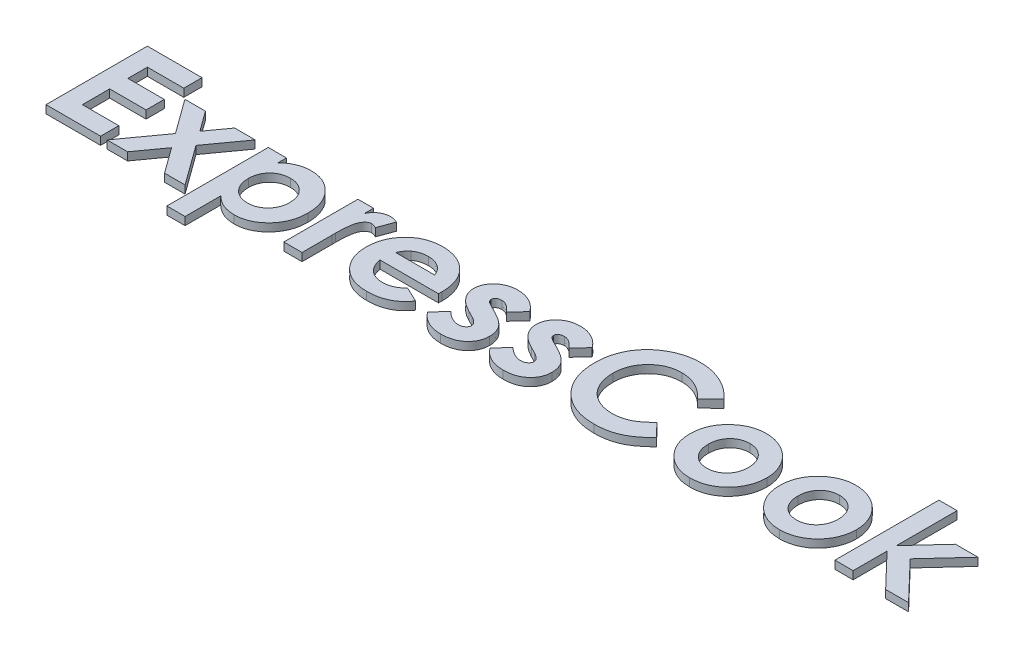
SolidWorks part; units mm, degrees
ref_plane "Front Plane" through (0, 0, 0) normal (0, 0, 1) x (1, 0, 0)
ref_plane "Top Plane" through (0, 0, 0) normal (0, 1, 0) x (1, 0, 0)
ref_plane "Right Plane" through (0, 0, 0) normal (1, 0, 0) x (0, 0, -1)
sketch "Sketch1" plane through (0, 0, 0) normal (0, 1, 0) x (1, 0, 0)
  text T0 "ExpressCook" font "Century Gothic" height in points 48
extrude "Boss-Extrude1" add sketch "Sketch1" along normal blind 1
